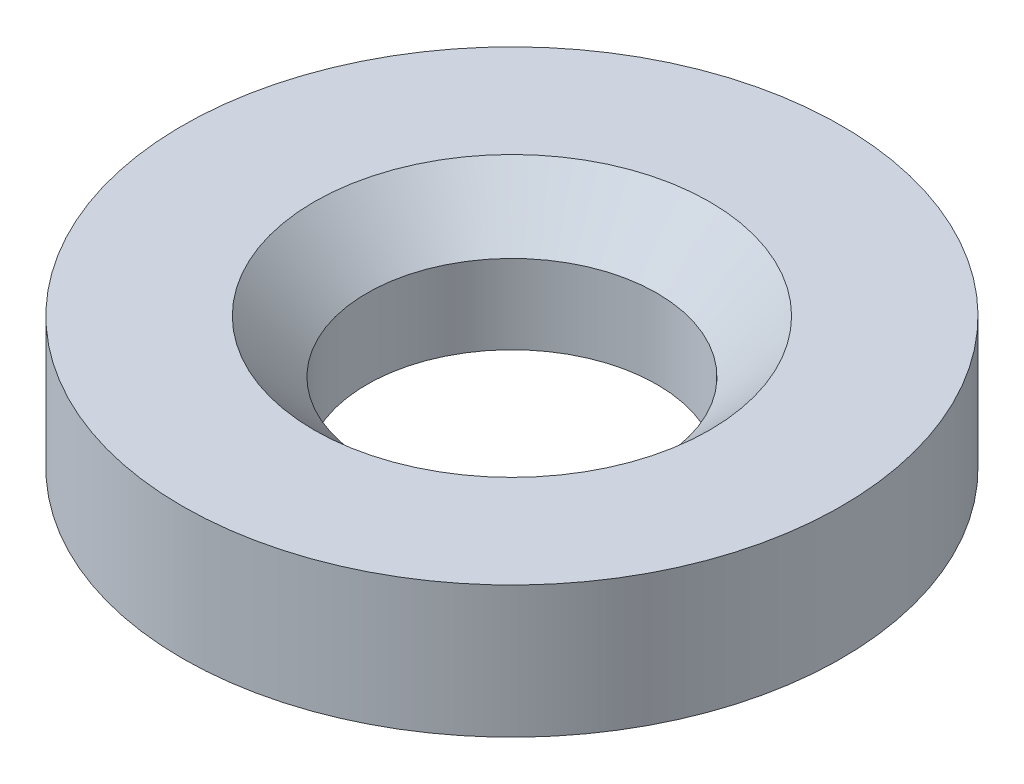
SolidWorks part; units mm, degrees
material "Delrin 2700 NC010, Low Viscosity Acetal Copolymer (SS)"
ref_plane "Front" through (0, 0, 0) normal (0, 0, 1) x (1, 0, 0)
ref_plane "Top" through (0, 0, 0) normal (0, 1, 0) x (1, 0, 0)
ref_plane "Right" through (0, 0, 0) normal (1, 0, 0) x (0, 0, -1)
sketch "Sketch1" plane through (0, 0, 0) normal (0, 1, 0) x (1, 0, 0)
  circle A0 centre (0, 0) radius 1.1
  circle A1 centre (0, 0) radius 2.5
  dimension "D1" = 2.2
  dimension "D2" = 5
extrude "Boss-Extrude1" add sketch "Sketch1" along normal blind 1
sketch "Sketch2" plane through (0, 0, 0) normal (0, 0, 1) x (1, 0, 0)
  line L0 (0, 0) -> (0, 1) construction
  line L1 (1.1, 1) -> (-1.1, 1) construction
  line L2 (-1.5, 1) -> (1.5, 1)
  line L3 (-1.5, 1) -> (-1.1, 0.6)
  line L4 (-1.1, 0) -> (1.1, 0)
  line L5 (-1.1, 0) -> (-1.1, 1)
  line L6 (-1.1, 1) -> (1.1, 1)
  line L7 (1.1, 0) -> (1.1, 1)
  line L8 (-1.1, 0) -> (1.1, 1) construction
  line L9 (-1.1, 1) -> (1.1, 0) construction
  line L10 (1.5, 1) -> (1.1, 0.6)
  point P7 (0, 1)
  point P9 (0, 0.5)
  dimension "D1" = 3
  dimension "D2" = 2.2
  dimension "D3" = 90
revolve "Cut-Revolve1" cut sketch "Sketch2" angle 360 about L0
